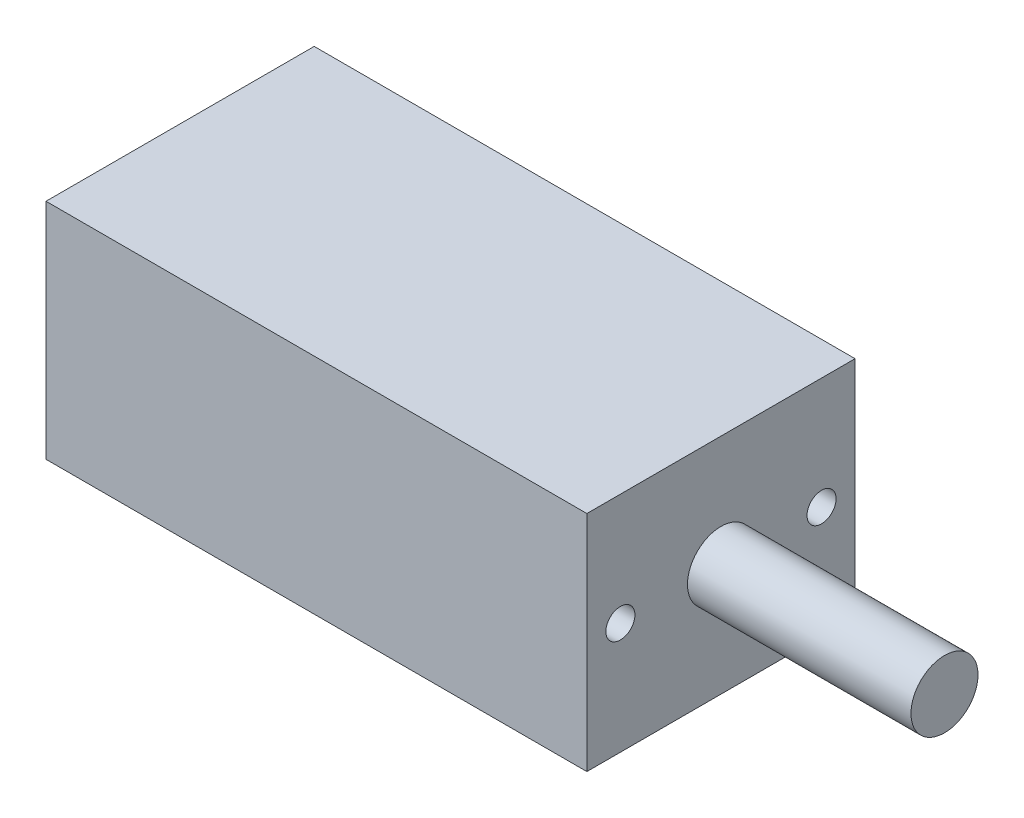
SolidWorks part; units mm, degrees
ref_plane "Front" through (0, 0, 0) normal (0, 0, 1) x (1, 0, 0)
ref_plane "Top" through (0, 0, 0) normal (0, 1, 0) x (1, 0, 0)
ref_plane "Right" through (0, 0, 0) normal (1, 0, 0) x (0, 0, -1)
sketch "Sketch1" plane through (0, 0, 0) normal (1, 0, 0) x (0, 0, -1)
  line L1 (-6, 5) -> (6, 5)
  line L2 (-6, 5) -> (-6, -5)
  line L3 (-6, -5) -> (6, -5)
  line L4 (6, 5) -> (6, -5)
  line L5 (-6, 5) -> (6, -5) construction
  line L6 (-6, -5) -> (6, 5) construction
  point P0 (0, 0)
  dimension "D1" = 12
  dimension "D2" = 10
extrude "Boss-Extrude1" add sketch "Sketch1" along normal blind 24.2
sketch "Sketch2" plane through (24.2, 0, 0) normal (1, 0, 0) x (0, 0, -1)
  circle A0 centre (0, 0) radius 1.5
  dimension "D1" = 3
extrude "Boss-Extrude2" add sketch "Sketch2" along normal blind 10
sketch "Sketch3" plane through (24.2, 0, 0) normal (1, 0, 0) x (0, 0, -1)
  line L0 (-4.5, 0) -> (0, 0) construction
  line L1 (0, 0) -> (4.5, 0) construction
  circle A0 centre (-4.5, 0) radius 0.65
  circle A1 centre (4.5, 0) radius 0.65
  dimension "D2" = 1.3
  dimension "D1" = 9
extrude "Cut-Extrude1" cut sketch "Sketch3" against normal blind 1
